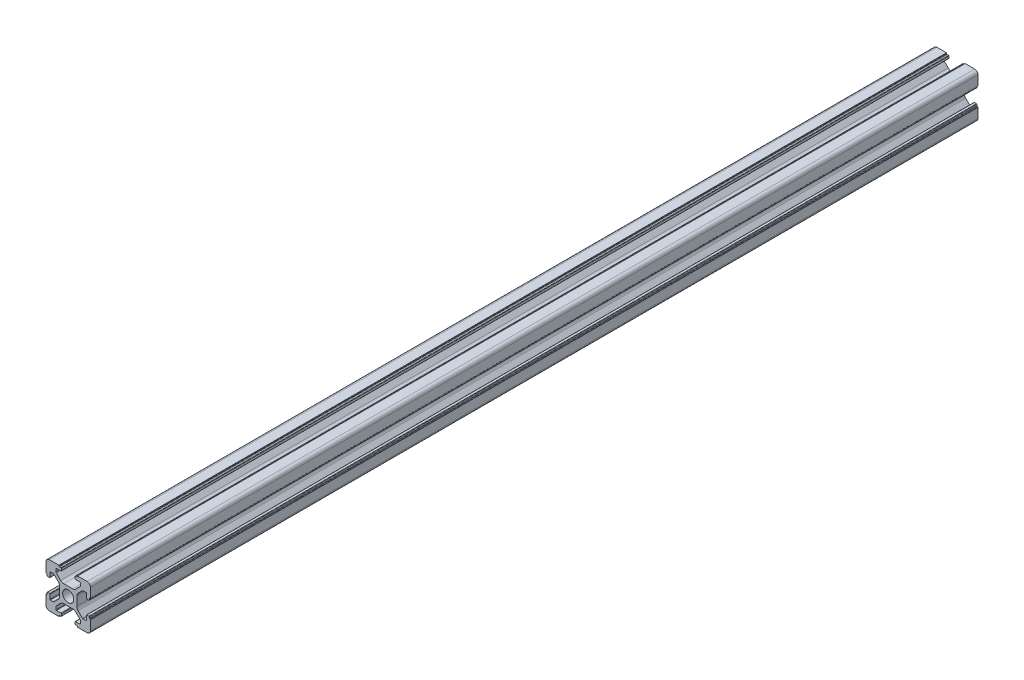
SolidWorks part; units mm, degrees
material "6063-T5"
ref_plane "Front Plane" through (0, 0, 0) normal (0, 0, 1) x (1, 0, 0)
ref_plane "Top Plane" through (0, 0, 0) normal (0, 1, 0) x (1, 0, 0)
ref_plane "Right Plane" through (0, 0, 0) normal (1, 0, 0) x (0, 0, -1)
sketch "Sketch1" plane through (0, 0, 0) normal (0, 0, -1) x (1, 0, 0)
  line L0 (1.5, 0) -> (5.8, 0)
  line L1 (20, 1.5) -> (20, 5.8)
  line L2 (18.5, 20) -> (14.2, 20)
  line L3 (0, 18.5) -> (0, 14.2)
  line L4 (14.2, 0) -> (18.5, 0)
  line L5 (13.3, 18.2) -> (15.3, 18.2)
  line L6 (20, 14.2) -> (20, 18.5)
  line L7 (0, 5.8) -> (0, 1.5)
  line L8 (6.7, 18.2) -> (4.7, 18.2)
  line L9 (1.8, 13.3) -> (1.8, 15.3)
  line L10 (19.3, 13.1) -> (18.4, 13.1)
  line L11 (19.3, 6.9) -> (18.4, 6.9)
  line L12 (6.9, 19.3) -> (6.9, 18.4)
  line L13 (13.1, 19.3) -> (13.1, 18.4)
  line L14 (0.7, 13.1) -> (1.6, 13.1)
  line L15 (0.7, 6.9) -> (1.6, 6.9)
  line L16 (13.4251, 14.4858) -> (15.4121, 16.4728)
  line L17 (14.4858, 13.4251) -> (16.4728, 15.4121)
  line L18 (14.4858, 6.5749) -> (16.4728, 4.5879)
  line L19 (13.4251, 5.5142) -> (15.4121, 3.5272)
  line L20 (6.5749, 5.5142) -> (4.5879, 3.5272)
  line L21 (5.5142, 6.5749) -> (3.5272, 4.5879)
  line L22 (5.5142, 13.4251) -> (3.5272, 15.4121)
  line L23 (6.5749, 14.4858) -> (4.5879, 16.4728)
  line L24 (6.9, 0.7) -> (6.9, 1.6)
  line L25 (13.1, 0.7) -> (13.1, 1.6)
  line L26 (5.8, 20) -> (1.5, 20)
  line L27 (1.8, 6.7) -> (1.8, 4.7)
  line L28 (6.7, 1.8) -> (4.7, 1.8)
  line L29 (13.3, 1.8) -> (15.3, 1.8)
  line L30 (18.2, 13.3) -> (18.2, 15.3)
  line L31 (18.2, 6.7) -> (18.2, 4.7)
  line L32 (2, 4.5) -> (3.3151, 4.5)
  line L33 (2, 15.5) -> (3.3151, 15.5)
  line L34 (4.5, 18) -> (4.5, 16.6849)
  line L35 (15.5, 18) -> (15.5, 16.6849)
  line L36 (18, 15.5) -> (16.6849, 15.5)
  line L37 (4.5, 2) -> (4.5, 3.3151)
  line L38 (15.5, 2) -> (15.5, 3.3151)
  line L39 (18, 4.5) -> (16.6849, 4.5)
  line L40 (7.9891, 13.9) -> (12.0109, 13.9)
  line L41 (7.9891, 6.1) -> (12.0109, 6.1)
  line L42 (13.9, 12.0109) -> (13.9, 7.9891)
  line L43 (6.1, 12.0109) -> (6.1, 7.9891)
  line L44 (19.5, 6.7) -> (19.5, 6.1)
  line L45 (5.9, 19.9) -> (5.9, 19.7)
  line L46 (6.1, 19.5) -> (6.7, 19.5)
  line L47 (14.1, 19.9) -> (14.1, 19.7)
  line L48 (13.9, 19.5) -> (13.3, 19.5)
  line L49 (0.1, 14.1) -> (0.3, 14.1)
  line L50 (0.5, 13.9) -> (0.5, 13.3)
  line L51 (0.1, 5.9) -> (0.3, 5.9)
  line L52 (0.5, 6.1) -> (0.5, 6.7)
  line L53 (19.9, 14.1) -> (19.7, 14.1)
  line L54 (19.5, 13.9) -> (19.5, 13.3)
  line L55 (19.7, 5.9) -> (19.9, 5.9)
  line L56 (14.1, 0.1) -> (14.1, 0.3)
  line L57 (13.9, 0.5) -> (13.3, 0.5)
  line L58 (6.7, 0.5) -> (6.1, 0.5)
  line L59 (5.9, 0.3) -> (5.9, 0.1)
  circle A0 centre (10, 10) radius 2.5
  arc A1 (18.5, 0) -> (20, 1.5) centre (18.5, 1.5) ccw
  arc A2 (1.5, 0) -> (0, 1.5) centre (1.5, 1.5) cw
  arc A3 (20, 18.5) -> (18.5, 20) centre (18.5, 18.5) ccw
  arc A4 (1.5, 20) -> (0, 18.5) centre (1.5, 18.5) ccw
  arc A5 (12.0109, 6.1) -> (13.4251, 5.5142) centre (12.0109, 4.1) cw
  arc A6 (13.9, 7.9891) -> (14.4858, 6.5749) centre (15.9, 7.9891) ccw
  arc A7 (13.9, 12.0109) -> (14.4858, 13.4251) centre (15.9, 12.0109) cw
  arc A8 (12.0109, 13.9) -> (13.4251, 14.4858) centre (12.0109, 15.9) ccw
  arc A9 (7.9891, 13.9) -> (6.5749, 14.4858) centre (7.9891, 15.9) cw
  arc A10 (6.1, 7.9891) -> (5.5142, 6.5749) centre (4.1, 7.9891) cw
  arc A11 (6.1, 12.0109) -> (5.5142, 13.4251) centre (4.1, 12.0109) ccw
  arc A12 (13.1, 1.6) -> (13.3, 1.8) centre (13.3, 1.6) cw
  arc A13 (6.9, 1.6) -> (6.7, 1.8) centre (6.7, 1.6) ccw
  arc A14 (6.1, 0.5) -> (5.9, 0.3) centre (6.1, 0.3) ccw
  arc A15 (6.7, 0.5) -> (6.9, 0.7) centre (6.7, 0.7) ccw
  arc A16 (1.6, 6.9) -> (1.8, 6.7) centre (1.6, 6.7) cw
  arc A17 (0.5, 6.7) -> (0.7, 6.9) centre (0.7, 6.7) cw
  arc A18 (0.5, 13.3) -> (0.7, 13.1) centre (0.7, 13.3) ccw
  arc A19 (1.6, 13.1) -> (1.8, 13.3) centre (1.6, 13.3) ccw
  arc A20 (6.7, 19.5) -> (6.9, 19.3) centre (6.7, 19.3) cw
  arc A21 (6.9, 18.4) -> (6.7, 18.2) centre (6.7, 18.4) cw
  arc A22 (13.1, 18.4) -> (13.3, 18.2) centre (13.3, 18.4) ccw
  arc A23 (13.3, 19.5) -> (13.1, 19.3) centre (13.3, 19.3) ccw
  arc A24 (18.4, 13.1) -> (18.2, 13.3) centre (18.4, 13.3) cw
  arc A25 (19.5, 13.3) -> (19.3, 13.1) centre (19.3, 13.3) cw
  arc A26 (19.5, 6.7) -> (19.3, 6.9) centre (19.3, 6.7) ccw
  arc A27 (14.1, 0.3) -> (13.9, 0.5) centre (13.9, 0.3) ccw
  arc A28 (19.5, 6.1) -> (19.7, 5.9) centre (19.7, 6.1) ccw
  arc A29 (5.9, 19.7) -> (6.1, 19.5) centre (6.1, 19.7) ccw
  arc A30 (14.1, 19.7) -> (13.9, 19.5) centre (13.9, 19.7) cw
  arc A31 (19.7, 14.1) -> (19.5, 13.9) centre (19.7, 13.9) ccw
  arc A32 (13.3, 0.5) -> (13.1, 0.7) centre (13.3, 0.7) cw
  arc A33 (0.3, 14.1) -> (0.5, 13.9) centre (0.3, 13.9) cw
  arc A34 (0.3, 5.9) -> (0.5, 6.1) centre (0.3, 6.1) ccw
  arc A35 (0, 5.8) -> (0.1, 5.9) centre (0.1, 5.8) cw
  arc A36 (5.9, 0.1) -> (5.8, 0) centre (5.8, 0.1) cw
  arc A37 (14.1, 0.1) -> (14.2, 0) centre (14.2, 0.1) ccw
  arc A38 (19.9, 5.9) -> (20, 5.8) centre (19.9, 5.8) cw
  arc A39 (20, 14.2) -> (19.9, 14.1) centre (19.9, 14.2) cw
  arc A40 (14.2, 20) -> (14.1, 19.9) centre (14.2, 19.9) ccw
  arc A41 (5.8, 20) -> (5.9, 19.9) centre (5.8, 19.9) cw
  arc A42 (0, 14.2) -> (0.1, 14.1) centre (0.1, 14.2) ccw
  arc A43 (18.4, 6.9) -> (18.2, 6.7) centre (18.4, 6.7) ccw
  arc A44 (1.8, 15.3) -> (2, 15.5) centre (2, 15.3) cw
  arc A45 (1.8, 4.7) -> (2, 4.5) centre (2, 4.7) ccw
  arc A46 (4.7, 1.8) -> (4.5, 2) centre (4.7, 2) cw
  arc A47 (15.3, 1.8) -> (15.5, 2) centre (15.3, 2) ccw
  arc A48 (18.2, 4.7) -> (18, 4.5) centre (18, 4.7) cw
  arc A49 (18.2, 15.3) -> (18, 15.5) centre (18, 15.3) ccw
  arc A50 (15.3, 18.2) -> (15.5, 18) centre (15.3, 18) cw
  arc A51 (4.7, 18.2) -> (4.5, 18) centre (4.7, 18) ccw
  arc A52 (7.9891, 6.1) -> (6.5749, 5.5142) centre (7.9891, 4.1) ccw
  arc A53 (3.3151, 15.5) -> (3.5272, 15.4121) centre (3.3151, 15.2) cw
  arc A54 (4.5, 16.6849) -> (4.5879, 16.4728) centre (4.8, 16.6849) ccw
  arc A55 (15.5, 16.6849) -> (15.4121, 16.4728) centre (15.2, 16.6849) cw
  arc A56 (16.6849, 15.5) -> (16.4728, 15.4121) centre (16.6849, 15.2) ccw
  arc A57 (16.6849, 4.5) -> (16.4728, 4.5879) centre (16.6849, 4.8) cw
  arc A58 (15.5, 3.3151) -> (15.4121, 3.5272) centre (15.2, 3.3151) ccw
  arc A59 (4.5, 3.3151) -> (4.5879, 3.5272) centre (4.8, 3.3151) cw
  arc A60 (3.3151, 4.5) -> (3.5272, 4.5879) centre (3.3151, 4.8) ccw
  point P67 (0, 0)
  point P125 (14.1, 19.5)
extrude "Boss-Extrude1" add sketch "Sketch1" along normal blind 400 contours L23 A54 L34 A51 L8 A21 L12 A20 L46 A29 L45 A41 L26 A4 L3 A42 L49 A33 L50 A18 L14 A19 L9 A44 L33 A53 L22 A11 L43 A10 L21 A60 L32 A45 L27 A16 L15 A17 L52 A34 L51 A35 L7 A2 L0 A36 L59 A14 L58 A15 L24 A13 L28 A46 L37 A59 L20 A52 L41 A5 L19 A58 L38 A47 L29 A12 L25 A32 L57 A27 L56 A37 L4 A1 L1 A38 L55 A28 L44 A26 L11 A43 L31 A48 L39 A57 L18 A6 L42 A7 L17 A56 L36 A49 L30 A24 L10 A25 L54 A31 L53 A39 L6 A3 L2 A40 L47 A30 L48 A23 L13 A22 L5 A50 L35 A55 L16 A8 L40 A9 | A0
